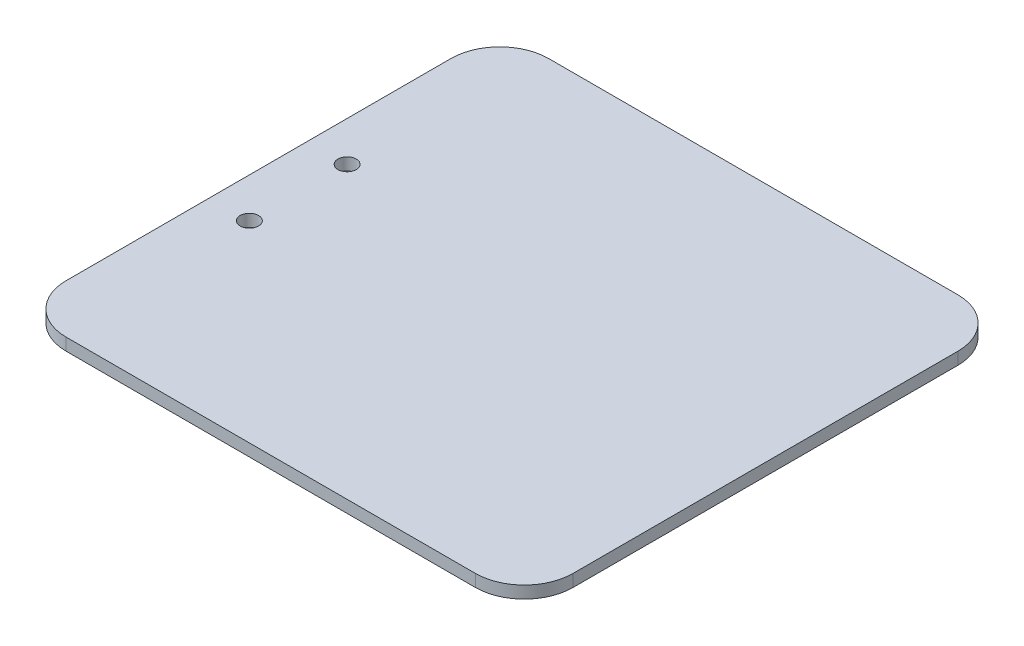
SolidWorks part; units mm, degrees
ref_plane "Front Plane" through (0, 0, 0) normal (0, 0, 1) x (1, 0, 0)
ref_plane "Top Plane" through (0, 0, 0) normal (0, 1, 0) x (1, 0, 0)
ref_plane "Right Plane" through (0, 0, 0) normal (1, 0, 0) x (0, 0, -1)
sketch "Sketch1" plane through (0, 0, 0) normal (0, 1, 0) x (1, 0, 0)
  line L0 (0, 39.5) -> (83, 39.5) construction
  line L1 (8, 0) -> (75, 0)
  line L2 (0, 8) -> (0, 71)
  line L3 (8, 79) -> (75, 79)
  line L4 (83, 8) -> (83, 71)
  line L5 (41.5, 79) -> (41.5, 0) construction
  circle A0 centre (6.5, 47.5) radius 1.5
  circle A1 centre (6.5, 31.5) radius 1.5
  arc A2 (8, 0) -> (0, 8) centre (8, 8) cw
  arc A3 (75, 0) -> (83, 8) centre (75, 8) ccw
  arc A4 (75, 79) -> (83, 71) centre (75, 71) cw
  arc A5 (0, 71) -> (8, 79) centre (8, 71) cw
  point P17 (0, 0)
  point P20 (83, 0)
  point P25 (0, 79)
  dimension "D3" = 3
  dimension "D6" = 8
  dimension "D1" = 83
  dimension "D2" = 79
  dimension "D4" = 6.5
  dimension "D5" = 8
extrude "Boss-Extrude1" add sketch "Sketch1" along normal blind 2
